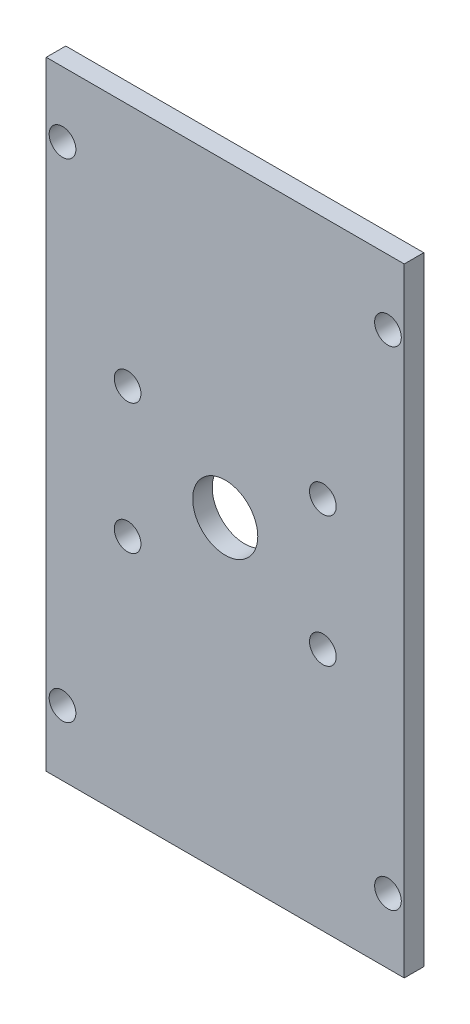
SolidWorks part; units mm, degrees
ref_plane "Front Plane" through (0, 0, 0) normal (0, 0, 1) x (1, 0, 0)
ref_plane "Top Plane" through (0, 0, 0) normal (0, 1, 0) x (1, 0, 0)
ref_plane "Right Plane" through (0, 0, 0) normal (1, 0, 0) x (0, 0, -1)
sketch "Sketch1" plane through (0, 0, 0) normal (0, 0, 1) x (1, 0, 0)
  line L1 (-55, 95) -> (55, 95)
  line L2 (-55, 95) -> (-55, -95)
  line L3 (-55, -95) -> (55, -95)
  line L4 (55, 95) -> (55, -95)
  line L5 (-55, 95) -> (55, -95) construction
  line L6 (-55, -95) -> (55, 95) construction
  point P0 (0, 0)
  dimension "D1" = 110
  dimension "D2" = 190
extrude "Boss-Extrude1" add sketch "Sketch1" along normal blind 6
sketch "Sketch3" plane through (0, 0, 6) normal (0, 0, 1) x (1, 0, 0)
  line L0 (-55, 75) -> (55, 75) construction
  line L1 (-55, 95) -> (-55, -95) construction
  line L2 (55, -95) -> (55, 95) construction
  line L3 (0, 95) -> (0, -95) construction
  line L4 (55, 95) -> (-55, 95) construction
  line L5 (-55, -95) -> (55, -95) construction
  line L6 (-55, -75) -> (55, -75) construction
  circle A0 centre (0, 0) radius 10
  point P14 (-50, 75)
  point P15 (50, 75)
  point P16 (-50, -75)
  point P17 (50, -75)
  dimension "D5" = 20
  dimension "D1" = 20
  dimension "D2" = 20
  dimension "D3" = 100
  dimension "D4" = 100
hole_wizard "M8 Clearance Hole1" positions "3DSketch2" profile "Sketch4" hole size "M8" standard "ANSI Metric" end condition up to next
sketch3d "3DSketch2"
  point P0 (-50, 75, 6)
  point P3 (50, 75, 6)
  point P6 (50, -75, 6)
  point P9 (-50, -75, 6)
sketch "Sketch4" plane through (-50, 75, 6) normal (1, 0, 0) x (0, -1, 0)
  line L0 (0, 0) -> (0, 6)
  line L1 (0, 6) -> (4.1, 6)
  line L2 (4.1, 6) -> (4.1, 0)
  line L5 (4.1, 0) -> (0, 0)
  line L11 (0, -6.35) -> (0, 107.95) construction
  dimension "Thru Hole Dia." = 8.2
  dimension "Thru Hole Depth" = 6
extrude "Cut-Extrude1" cut sketch "Sketch3" against normal up to next
sketch "Sketch5" plane through (0, 0, 6) normal (0, 0, 1) x (1, 0, 0)
  line L1 (-30, 20) -> (30, 20) construction
  line L2 (-30, 20) -> (-30, -20) construction
  line L3 (-30, -20) -> (30, -20) construction
  line L4 (30, 20) -> (30, -20) construction
  line L5 (-30, 20) -> (30, -20) construction
  line L6 (-30, -20) -> (30, 20) construction
  point P0 (0, 0)
  dimension "D1" = 60
  dimension "D2" = 40
hole_wizard "M8 Clearance Hole2" positions "3DSketch3" profile "Sketch6" hole size "M8" standard "ANSI Metric"
sketch3d "3DSketch3"
  point P0 (-30, 20, 6)
  point P3 (30, 20, 6)
  point P6 (30, -20, 6)
  point P9 (-30, -20, 6)
sketch "Sketch6" plane through (-30, 20, 6) normal (1, 0, 0) x (0, -1, 0)
  line L0 (0, 0) -> (0, 22.2135)
  line L1 (0, 22.2135) -> (4.1, 19.75)
  line L2 (4.1, 19.75) -> (4.1, 0)
  line L5 (4.1, 0) -> (0, 0)
  line L10 (0, 22.2135) -> (-4.1, 19.75) construction
  line L11 (0, -6.35) -> (0, 107.95) construction
  dimension "Hole Dia." = 8.2
  dimension "Hole Depth" = 19.75
  dimension "Drill Angle" = 118
